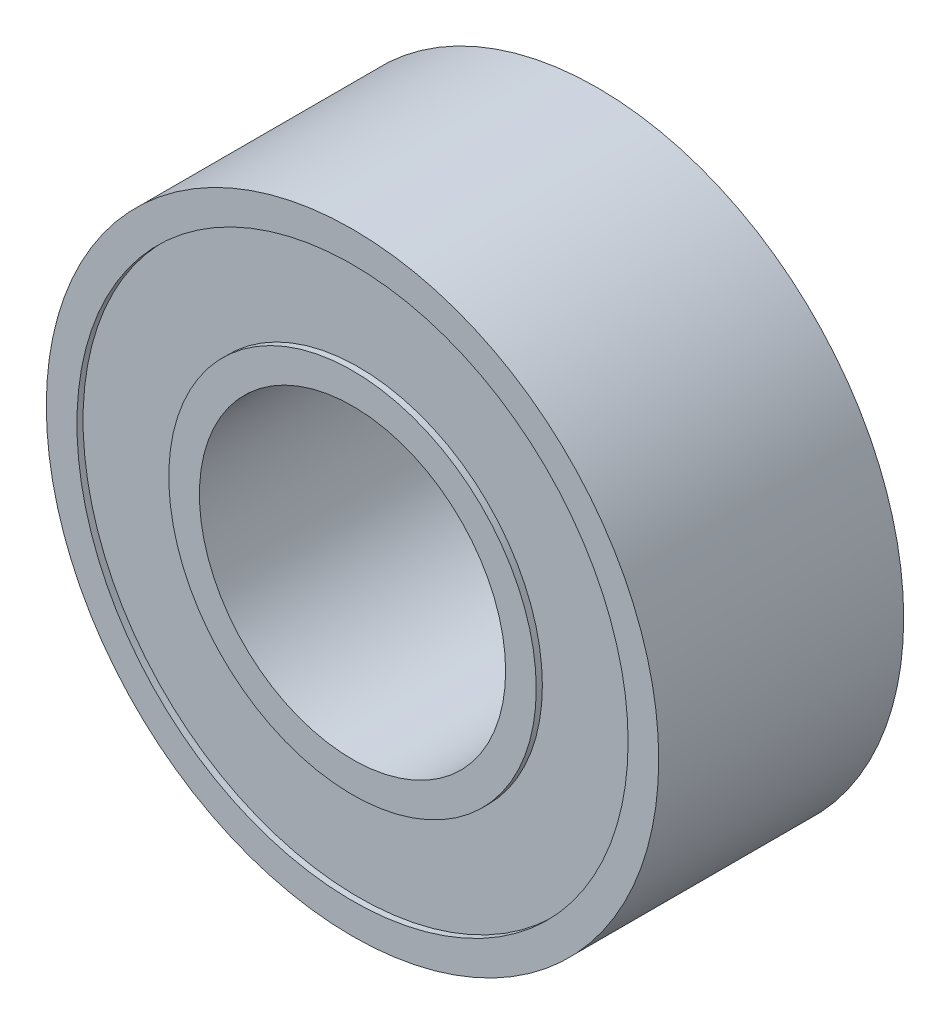
SolidWorks part; units mm, degrees
ref_plane "Front Plane" through (0, 0, 0) normal (0, 0, 1) x (1, 0, 0)
ref_plane "Top Plane" through (0, 0, 0) normal (0, 1, 0) x (1, 0, 0)
ref_plane "Right Plane" through (0, 0, 0) normal (1, 0, 0) x (0, 0, -1)
sketch "Sketch1" plane through (0, 0, 0) normal (0, 0, 1) x (1, 0, 0)
  circle A0 centre (0, 0) radius 5
  circle A1 centre (0, 0) radius 2.5
  dimension "D1" = 10
  dimension "D2" = 5
extrude "Boss-Extrude1" add sketch "Sketch1" along normal mid plane 4
sketch "Sketch2" plane through (0, 0, 2) normal (0, 0, 1) x (1, 0, 0)
  circle A2 centre (0, 0) radius 4.5
  circle A3 centre (0, 0) radius 4.5
  circle A5 centre (0, 0) radius 3
  circle A6 centre (0, 0) radius 3
  dimension "D1" = 0.5
  dimension "D2" = 0.5
extrude "Cut-Extrude1" cut sketch "Sketch2" against normal blind 0.1
mirror "Mirror1" about plane through (0, 0, 0) normal (0, 0, 1) of "Cut-Extrude1"
